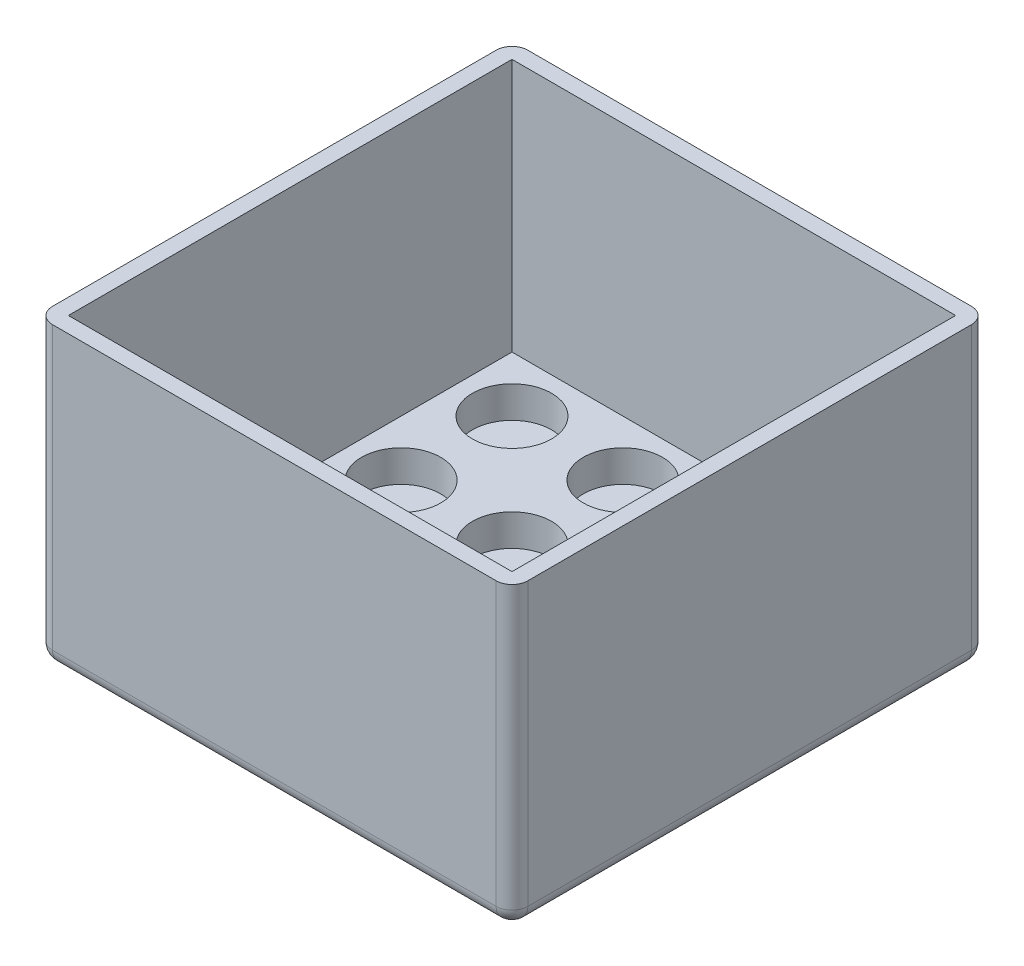
SolidWorks part; units mm, degrees
ref_plane "Front Plane" through (0, 0, 0) normal (0, 0, 1) x (1, 0, 0)
ref_plane "Top Plane" through (0, 0, 0) normal (0, 1, 0) x (1, 0, 0)
ref_plane "Right Plane" through (0, 0, 0) normal (1, 0, 0) x (0, 0, -1)
sketch "Sketch1" plane through (0, 0, 0) normal (0, 1, 0) x (1, 0, 0)
  line L1 (0, 0) -> (140, 0)
  line L2 (0, 0) -> (0, 140)
  line L3 (0, 140) -> (140, 140)
  line L4 (140, 0) -> (140, 140)
  line L5 (-5, 145) -> (145, 145)
  line L6 (-5, 145) -> (-5, -5)
  line L7 (-5, -5) -> (145, -5)
  line L8 (145, 145) -> (145, -5)
  dimension "D1" = 140
  dimension "D2" = 140
  dimension "D3" = 5
  dimension "D4" = 5
  dimension "D5" = 5
  dimension "D6" = 5
extrude "Boss-Extrude1" add sketch "Sketch1" along normal blind 90
sketch "Sketch2" plane through (0, 0, 0) normal (0, -1, 0) x (1, 0, 0)
  line L1 (145, -145) -> (-5, -145)
  line L2 (145, -145) -> (145, 5)
  line L3 (145, 5) -> (-5, 5)
  line L4 (-5, -145) -> (-5, 5)
extrude "Boss-Extrude2" add sketch "Sketch2" along normal blind 4
sketch "Sketch3" plane through (0, 0, 0) normal (0, 1, 0) x (1, 0, 0)
  line L0 (0, 140) -> (0, 0) construction
  line L1 (140, 140) -> (0, 140) construction
  circle A0 centre (17.5, 122.5) radius 12.5
  circle A1 centre (52.5, 122.5) radius 12.5
  circle A2 centre (87.5, 122.5) radius 12.5
  circle A3 centre (122.5, 122.5) radius 12.5
  circle A4 centre (52.5, 87.5) radius 12.5
  circle A5 centre (87.5, 87.5) radius 12.5
  circle A6 centre (122.5, 87.5) radius 12.5
  circle A7 centre (52.5, 52.5) radius 12.5
  circle A8 centre (87.5, 52.5) radius 12.5
  circle A9 centre (122.5, 52.5) radius 12.5
  circle A10 centre (52.5, 17.5) radius 12.5
  circle A11 centre (87.5, 17.5) radius 12.5
  circle A12 centre (122.5, 17.5) radius 12.5
  circle A13 centre (17.5, 87.5) radius 12.5
  circle A14 centre (17.5, 52.5) radius 12.5
  circle A15 centre (17.5, 17.5) radius 12.5
  line M3 (140, 140) -> (0, 140)
  line M4 (0, 140) -> (0, 0)
  line M5 (0, 0) -> (140, 0)
  line M6 (140, 0) -> (140, 140)
  dimension "D3" = 25
  dimension "D1" = 17.5
  dimension "D2" = 17.5
  dimension "D4" = 4
  dimension "D5" = 4
extrude "Boss-Extrude3" add sketch "Sketch3" along normal blind 10 contours A15 A14 A13 A12 A11 A10 A9 A8 A7 A6 A5 A4 A3 A2 A1 A0 M6 M3 M4 M5
fillet "Fillet1" radius 5 8 edges at (145, -4, -70) (70, -4, 5) (-5, -4, -70) (70, -4, -145) (-5, 43, -145) (145, 43, -145) (145, 43, 5) (-5, 43, 5)
